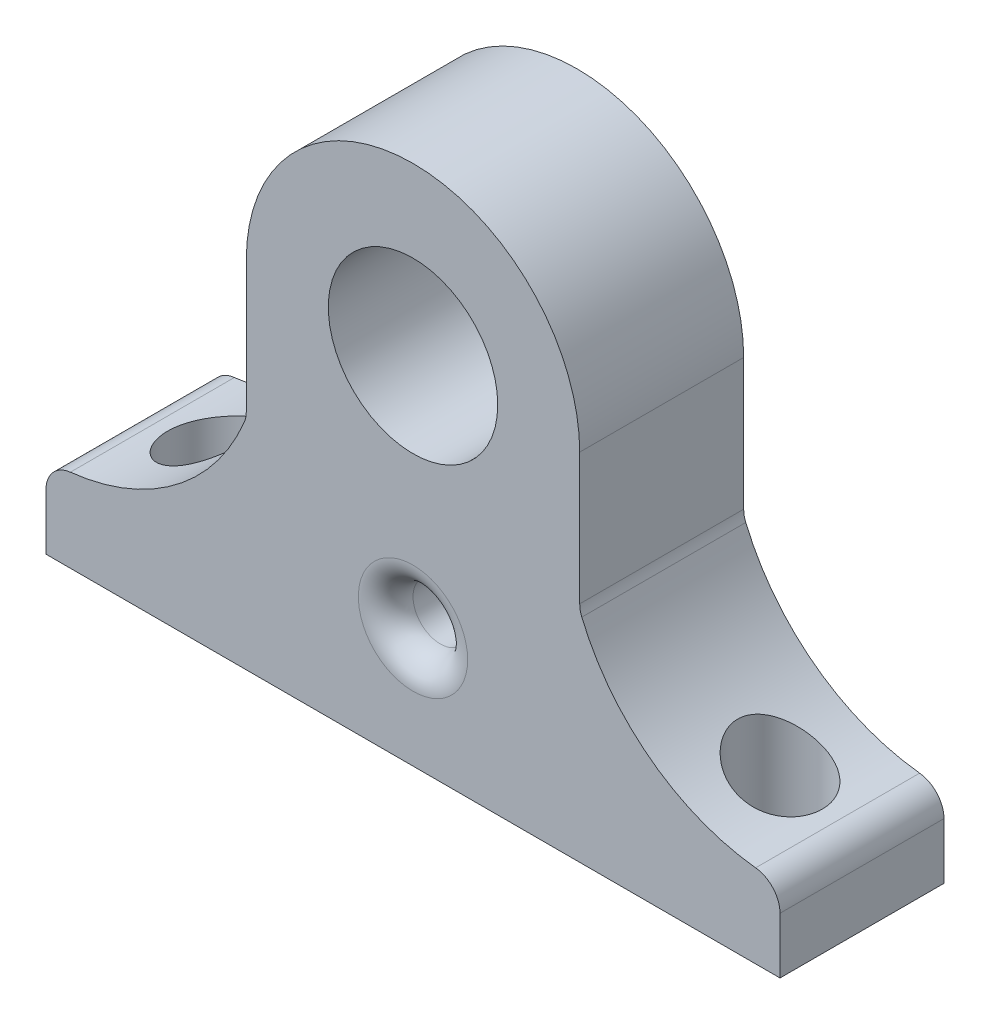
SolidWorks part; units mm, degrees
ref_plane "Front Plane" through (0, 0, 0) normal (0, 0, 1) x (1, 0, 0)
ref_plane "Top Plane" through (0, 0, 0) normal (0, 1, 0) x (1, 0, 0)
ref_plane "Right Plane" through (0, 0, 0) normal (1, 0, 0) x (0, 0, -1)
sketch "Sketch1" plane through (0, 0, 0) normal (0, 0, 1) x (1, 0, 0)
  line L0 (-6.1, 0) -> (-6.1, -4.8076)
  line L1 (-13.4293, -10) -> (-13.3356, -10)
  line L2 (0, 0) -> (0, -8.6294) construction
  line L3 (13.4293, -10) -> (13.3356, -10)
  line L4 (6.1, 0) -> (6.1, -4.8076)
  line L5 (-13.4293, -10) -> (-13.4293, -13)
  line L6 (13.4293, -10) -> (13.4293, -13)
  line L7 (-13.4293, -13) -> (13.4293, -13)
  line L8 (13.3356, -10) -> (13.4293, -10)
  line L9 (-13.3356, -10) -> (-13.4293, -10)
  circle A0 centre (0, 0) radius 3.1
  arc A1 (6.1, 0) -> (-6.1, 0) centre (0, 0) ccw
  arc A2 (-6.1766, -5.1913) -> (-13.4293, -10) centre (-13.3825, -2.1968) cw
  arc A3 (-6.1766, -5.1913) -> (-6.1, -4.8076) centre (-7.1, -4.8076) ccw
  arc A4 (6.1766, -5.1913) -> (6.1, -4.8076) centre (7.1, -4.8076) cw
  arc A5 (6.1766, -5.1913) -> (13.4293, -10) centre (13.3825, -2.1968) ccw
  circle A6 centre (0, -8.6294) radius 1
  circle A7 centre (0, 0) radius 6.1 construction
  dimension "D1" = 3
  dimension "D2" = 1
  dimension "D3" = 3
extrude "Boss-Extrude1" add sketch "Sketch1" along normal blind 6
sketch "Sketch2" plane through (0, -13, 0) normal (0, -1, 0) x (1, 0, 0)
  line L0 (-13.4293, 6) -> (-13.4293, 0) construction
  line L1 (-13.4293, 0) -> (-13.4293, 3) construction
  line L2 (-13.4293, 3) -> (13.4293, 3) construction
  line L3 (13.4293, 6) -> (13.4293, 0) construction
  line L4 (0, 3) -> (0, 1.9191) construction
  circle A0 centre (-10.4293, 3) radius 1.55
  circle A1 centre (10.4293, 3) radius 1.55
  dimension "D1" = 3.1
  dimension "D2" = 3
extrude "Cut-Extrude1" cut sketch "Sketch2" against normal through all both and the other way through all
fillet "Fillet1" radius 1 4 edges at (1, -8.6294, 6) (1, -8.6294, 0) (-13.4293, -10, 3) (13.4293, -10, 3)
